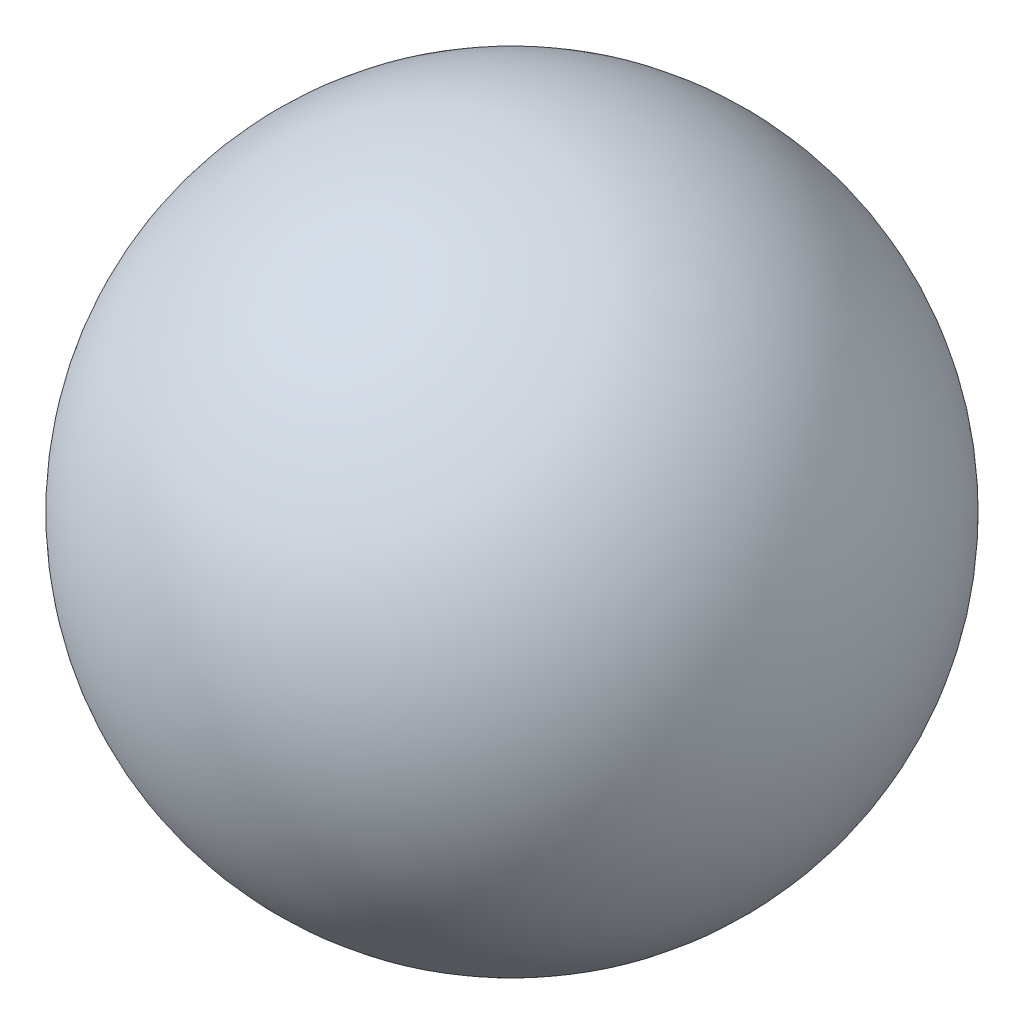
SolidWorks part; units mm, degrees
ref_plane "Front Plane" through (0, 0, 0) normal (0, 0, 1) x (1, 0, 0)
ref_plane "Top Plane" through (0, 0, 0) normal (0, 1, 0) x (1, 0, 0)
ref_plane "Right Plane" through (0, 0, 0) normal (1, 0, 0) x (0, 0, -1)
sketch "Sketch1" plane through (0, 0, 0) normal (1, 0, 0) x (0, 0, -1)
  line L0 (0, 50.8) -> (0, -50.8)
  arc A0 (0, -50.8) -> (0, 50.8) centre (0, 0) ccw
  dimension "D1" = 101.6
revolve "Revolve1" add sketch "Sketch1" angle 360 about L0
